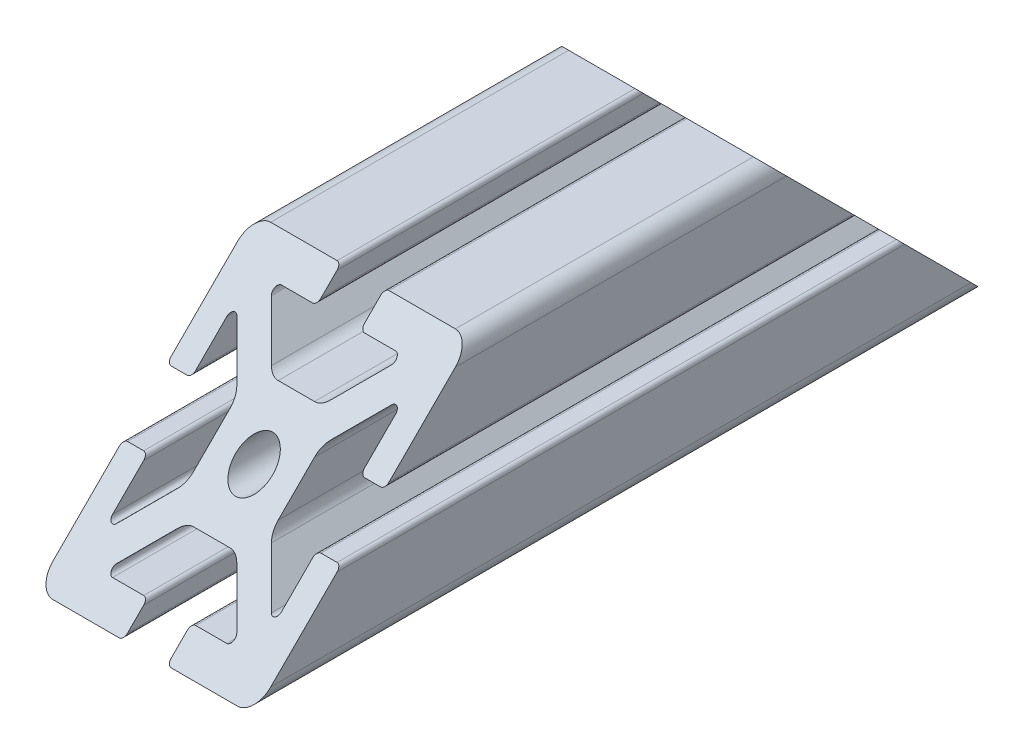
SolidWorks part; units mm, degrees
ref_plane "Front Plane" through (0, 0, 0) normal (0, 0, 1) x (1, 0, 0)
ref_plane "Top Plane" through (0, 0, 0) normal (0, 1, 0) x (1, 0, 0)
ref_plane "Right Plane" through (0, 0, 0) normal (1, 0, 0) x (0, 0, -1)
sketch "Sketch1" plane through (0, 0, 0) normal (0, 0, 1) x (1, 0, 0)
  line L0 (0, 20) -> (0, -20) construction
  line L1 (-20, 0) -> (20, 0) construction
  line L2 (-20, 16.952) -> (-20, 4.7625)
  line L3 (-16.952, 20) -> (-4.7625, 20)
  line L4 (-4.0005, 19.238) -> (-4.0005, 16.2662)
  line L5 (-4.7625, 15.5042) -> (-10.4856, 15.5042)
  line L6 (-11.0244, 14.2034) -> (-5.456, 8.6351)
  line L7 (-14.2034, 11.0244) -> (-8.6351, 5.456)
  line L8 (-15.5042, 10.4856) -> (-15.5042, 4.7625)
  line L9 (-16.2662, 4.0005) -> (-19.238, 4.0005)
  line L10 (0, 0) -> (-20, 20) construction
  line L11 (-3.3367, 7.7572) -> (3.3367, 7.7572)
  line L12 (-7.7572, 3.3367) -> (-7.7572, -3.3367)
  line L13 (16.2662, 4.0005) -> (19.238, 4.0005)
  line L14 (15.5042, 10.4856) -> (15.5042, 4.7625)
  line L15 (20, 16.952) -> (20, 4.7625)
  line L16 (16.952, 20) -> (4.7625, 20)
  line L17 (4.0005, 19.238) -> (4.0005, 16.2662)
  line L18 (4.7625, 15.5042) -> (10.4856, 15.5042)
  line L19 (7.7572, 3.3367) -> (7.7572, -3.3367)
  line L20 (11.0244, 14.2034) -> (5.456, 8.6351)
  line L21 (14.2034, 11.0244) -> (8.6351, 5.456)
  line L22 (-16.2662, -4.0005) -> (-19.238, -4.0005)
  line L23 (-15.5042, -10.4856) -> (-15.5042, -4.7625)
  line L24 (-14.2034, -11.0244) -> (-8.6351, -5.456)
  line L25 (-11.0244, -14.2034) -> (-5.456, -8.6351)
  line L26 (-4.7625, -15.5042) -> (-10.4856, -15.5042)
  line L27 (-4.0005, -19.238) -> (-4.0005, -16.2662)
  line L28 (-16.952, -20) -> (-4.7625, -20)
  line L29 (-20, -16.952) -> (-20, -4.7625)
  line L30 (20, -16.952) -> (20, -4.7625)
  line L31 (16.952, -20) -> (4.7625, -20)
  line L32 (4.0005, -19.238) -> (4.0005, -16.2662)
  line L33 (4.7625, -15.5042) -> (10.4856, -15.5042)
  line L34 (11.0244, -14.2034) -> (5.456, -8.6351)
  line L35 (14.2034, -11.0244) -> (8.6351, -5.456)
  line L36 (15.5042, -10.4856) -> (15.5042, -4.7625)
  line L37 (16.2662, -4.0005) -> (19.238, -4.0005)
  line L38 (-3.3367, -7.7572) -> (3.3367, -7.7572)
  circle A0 centre (0, 0) radius 3.4036
  arc A1 (-20, 16.952) -> (-16.952, 20) centre (-16.952, 16.952) cw
  arc A2 (-14.2034, 11.0244) -> (-15.5042, 10.4856) centre (-14.7422, 10.4856) ccw
  arc A3 (-10.4856, 15.5042) -> (-11.0244, 14.2034) centre (-10.4856, 14.7422) ccw
  arc A4 (-4.7625, 20) -> (-4.0005, 19.238) centre (-4.7625, 19.238) cw
  arc A5 (-20, 4.7625) -> (-19.238, 4.0005) centre (-19.238, 4.7625) ccw
  arc A6 (-15.5042, 4.7625) -> (-16.2662, 4.0005) centre (-16.2662, 4.7625) cw
  arc A7 (-4.0005, 16.2662) -> (-4.7625, 15.5042) centre (-4.7625, 16.2662) cw
  arc A8 (-3.3367, 7.7572) -> (-5.456, 8.6351) centre (-3.3367, 10.7544) cw
  arc A9 (-7.7572, 3.3367) -> (-8.6351, 5.456) centre (-10.7544, 3.3367) ccw
  arc A10 (15.5042, 4.7625) -> (16.2662, 4.0005) centre (16.2662, 4.7625) ccw
  arc A11 (20, 4.7625) -> (19.238, 4.0005) centre (19.238, 4.7625) cw
  arc A12 (20, 16.952) -> (16.952, 20) centre (16.952, 16.952) ccw
  arc A13 (4.7625, 20) -> (4.0005, 19.238) centre (4.7625, 19.238) ccw
  arc A14 (4.0005, 16.2662) -> (4.7625, 15.5042) centre (4.7625, 16.2662) ccw
  arc A15 (3.3367, 7.7572) -> (5.456, 8.6351) centre (3.3367, 10.7544) ccw
  arc A16 (7.7572, 3.3367) -> (8.6351, 5.456) centre (10.7544, 3.3367) cw
  arc A17 (14.2034, 11.0244) -> (15.5042, 10.4856) centre (14.7422, 10.4856) cw
  arc A18 (10.4856, 15.5042) -> (11.0244, 14.2034) centre (10.4856, 14.7422) cw
  arc A19 (-7.7572, -3.3367) -> (-8.6351, -5.456) centre (-10.7544, -3.3367) cw
  arc A20 (-3.3367, -7.7572) -> (-5.456, -8.6351) centre (-3.3367, -10.7544) ccw
  arc A21 (-4.0005, -16.2662) -> (-4.7625, -15.5042) centre (-4.7625, -16.2662) ccw
  arc A22 (-15.5042, -4.7625) -> (-16.2662, -4.0005) centre (-16.2662, -4.7625) ccw
  arc A23 (-20, -4.7625) -> (-19.238, -4.0005) centre (-19.238, -4.7625) cw
  arc A24 (-4.7625, -20) -> (-4.0005, -19.238) centre (-4.7625, -19.238) ccw
  arc A25 (-10.4856, -15.5042) -> (-11.0244, -14.2034) centre (-10.4856, -14.7422) cw
  arc A26 (-14.2034, -11.0244) -> (-15.5042, -10.4856) centre (-14.7422, -10.4856) cw
  arc A27 (-20, -16.952) -> (-16.952, -20) centre (-16.952, -16.952) ccw
  arc A28 (20, -16.952) -> (16.952, -20) centre (16.952, -16.952) cw
  arc A29 (14.2034, -11.0244) -> (15.5042, -10.4856) centre (14.7422, -10.4856) ccw
  arc A30 (10.4856, -15.5042) -> (11.0244, -14.2034) centre (10.4856, -14.7422) ccw
  arc A31 (4.7625, -20) -> (4.0005, -19.238) centre (4.7625, -19.238) cw
  arc A32 (20, -4.7625) -> (19.238, -4.0005) centre (19.238, -4.7625) ccw
  arc A33 (15.5042, -4.7625) -> (16.2662, -4.0005) centre (16.2662, -4.7625) cw
  arc A34 (4.0005, -16.2662) -> (4.7625, -15.5042) centre (4.7625, -16.2662) cw
  arc A35 (3.3367, -7.7572) -> (5.456, -8.6351) centre (3.3367, -10.7544) cw
  arc A36 (7.7572, -3.3367) -> (8.6351, -5.456) centre (10.7544, -3.3367) ccw
  point P29 (-20, 4.0005)
  point P32 (-15.5042, 4.0005)
  point P36 (-4.5782, 7.7572)
  point P68 (0, 7.7572)
  dimension "D4" = 6.8072
  dimension "D5" = 3.048
  dimension "D6" = 0.762
  dimension "D9" = 0.762
  dimension "D10" = 0.762
  dimension "D11" = 4.4958
  dimension "D13" = 2.9972
  dimension "D1" = 40
  dimension "D2" = 40
  dimension "D3" = 12.2428
  dimension "D7" = 8.001
  dimension "D8" = 4.4958
extrude "Extrude1" add sketch "Sketch1" along normal mid plane 2438.4
sketch "Sketch2" plane through (20, 0, 0) normal (1, 0, 0) x (0, 0, -1)
  line L0 (1084.4962, -20) -> (692.3778, -20)
  line L1 (-1219.2, -20) -> (1219.2, -20) construction
  line L2 (1219.2, -20) -> (1179.2, 20)
  line L3 (1124.4962, 20) -> (1084.4962, -20)
  line L4 (1179.2, 20) -> (1219.2, 20)
  line L5 (-1219.2, 20) -> (1219.2, 20) construction
  line L6 (1219.2, 20) -> (1219.2, -20)
  line L7 (1084.4962, -20) -> (-1219.2, -20)
  line L8 (-1219.2, -20) -> (-1219.2, 20)
  line L9 (-1219.2, 20) -> (1124.4962, 20)
  point P0 (1219.2, -20)
extrude "Cut-Extrude1" cut sketch "Sketch2" against normal through all contours L4 L6 L2 | L7 L8 L9 L3
equation "\"D2@Sketch1\" = \"D1@Sketch1\""
